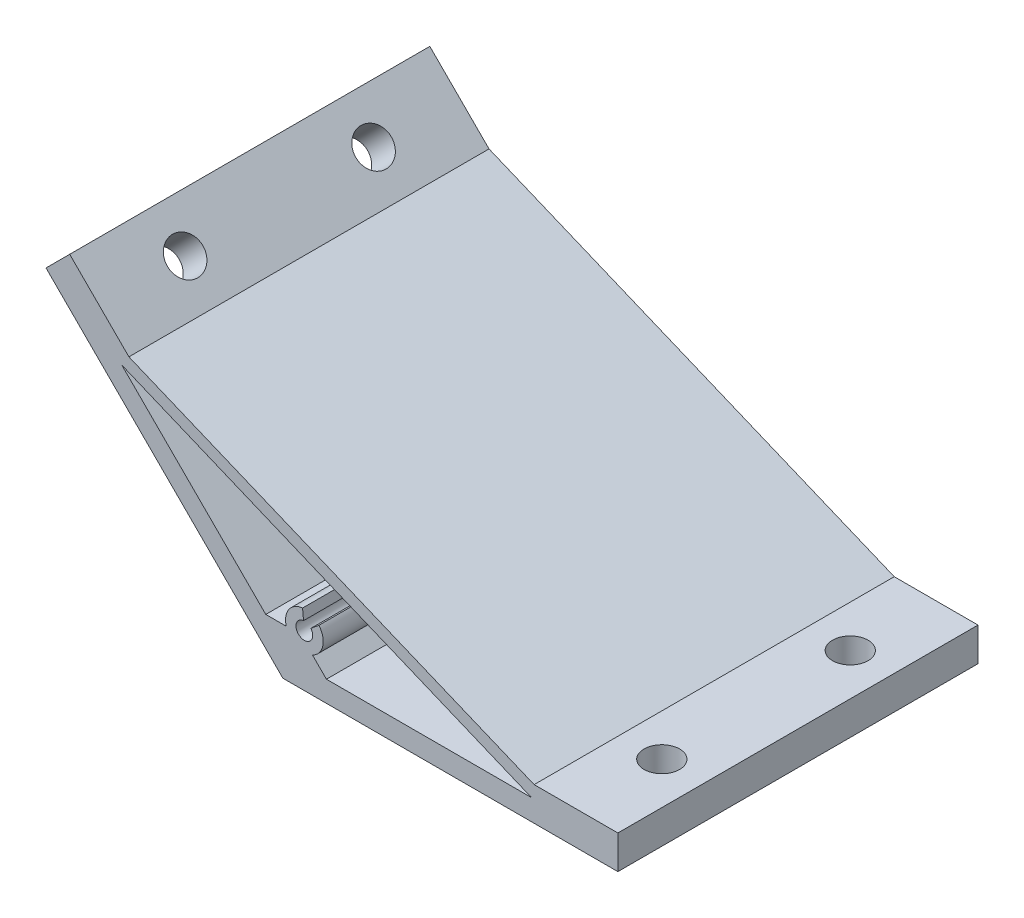
SolidWorks part; units mm, degrees
ref_plane "前视基准面" through (0, 0, 0) normal (0, 0, 1) x (1, 0, 0)
ref_plane "上视基准面" through (0, 0, 0) normal (0, 1, 0) x (1, 0, 0)
ref_plane "右视基准面" through (0, 0, 0) normal (1, 0, 0) x (0, 0, -1)
sketch "草图1" plane through (0, 0, 0) normal (0, 0, 1) x (1, 0, 0)
  line L0 (6992.6877, -1288.6549) -> (7072.6877, -1288.6549)
  line L1 (7003.0909, -1283.6549) -> (7052.0909, -1283.6549)
  line L2 (7052.6877, -1280.6549) -> (7072.6877, -1280.6549)
  line L3 (7003.0909, -1283.6549) -> (7029.4034, -1283.6549)
  line L4 (7072.6877, -1288.6549) -> (7072.6877, -1280.6549)
  line L5 (6997.6265, -1274.2736) -> (6997.3838, -1271.7854)
  line L6 (6999.3656, -1274.9939) -> (7001.2967, -1273.4062)
  line L7 (6992.6877, -1288.6549) -> (6936.1191, -1232.0864)
  line L8 (6988.6024, -1277.4986) -> (6954.2187, -1243.1149)
  line L9 (6955.9181, -1240.5717) -> (6941.776, -1226.4295)
  line L10 (6936.1191, -1232.0864) -> (6941.776, -1226.4295)
  line L11 (6955.9181, -1240.5717) -> (7052.6877, -1280.6549)
  line L12 (6954.2187, -1243.1149) -> (7052.0909, -1283.6549)
  line L13 (7052.0909, -1283.6549) -> (7009.0909, -1283.6549)
  line L14 (7003.0909, -1283.6549) -> (6999.7605, -1280.3246)
  line L15 (6988.6024, -1277.4986) -> (6993.4934, -1277.4986)
  arc A0 (6997.3838, -1271.7854) -> (6993.4934, -1277.4986) centre (6997.8207, -1276.2641) ccw
  arc A1 (6999.7605, -1280.3246) -> (7001.2967, -1273.4062) centre (6997.8207, -1276.2641) ccw
  arc A2 (6997.6265, -1274.2736) -> (6999.3656, -1274.9939) centre (6997.8207, -1276.2641) ccw
extrude "凸台-拉伸1" add sketch "草图1" along normal mid plane 86 contours L11 L9 L10 L7 L0 L4 L2 A2 L5 A0 L15 L8 L12 L1 L3 L14 A1 L6
hole_wizard "Ø8.5 (8.5) 直径孔1" positions "草图3" profile "草图2" hole size "Ø8.5" standard "GB" end condition through all
sketch "草图3" plane through (2852.0164, 2852.0164, 0) normal (-0.7071, -0.7071, 0) x (0.7071, -0.7071, 0)
  line L1 (5775.7935, 43) -> (5775.7935, -43) construction
  line L2 (5795.7935, -43) -> (5775.7935, -43) construction
  point P1 (5785.7935, -22.5)
  point P18 (5785.7935, 22.5)
  dimension "D1" = 10
  dimension "D2" = 20.5
  dimension "D3" = 2
sketch "草图2" plane through (6943.1902, -1239.1575, -22.5) normal (0, 0, 1) x (0.7071, -0.7071, 0)
  line L0 (0, 0) -> (0, 62.2254)
  line L1 (0, 62.2254) -> (4.25, 62.2254)
  line L2 (4.25, 62.2254) -> (4.25, 0)
  line L5 (4.25, 0) -> (0, 0)
  line L11 (0, -6.35) -> (0, 107.95) construction
  dimension "通孔孔直径" = 8.5
  dimension "通孔孔深度" = 62.2254
sketch "草图4" plane through (580.0623, 1400.3943, 0) normal (0.3827, 0.9239, 0) x (0.9239, -0.3827, 0)
  line L0 (6953.5479, -43) -> (6953.5479, 43) construction
  line L1 (6901.1766, -43) -> (7005.9192, -43) construction
  line L2 (6901.1766, 43) -> (7005.9192, 43) construction
ref_plane "基准面1" through (6424.2406, -2661.0076, 0) normal (-0.9239, 0.3827, 0) x (0, 0, 1)
mirror "镜向1" about plane through (6424.2406, -2661.0076, 0) normal (-0.9239, 0.3827, 0) of "Ø8.5 (8.5) 直径孔1"
